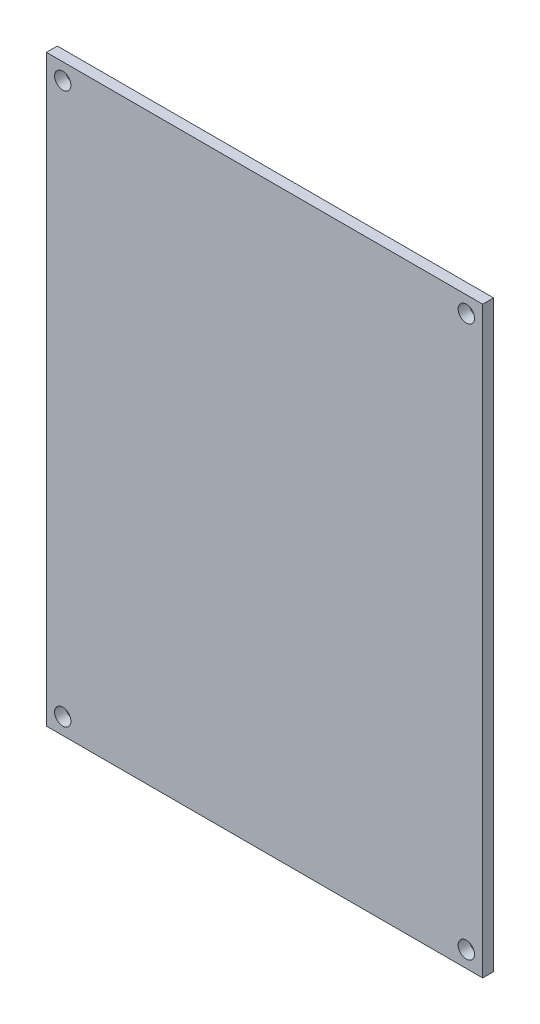
SolidWorks part; units mm, degrees
ref_plane "Ön Düzlem" through (0, 0, 0) normal (0, 0, 1) x (1, 0, 0)
ref_plane "Üst Düzlem" through (0, 0, 0) normal (0, 1, 0) x (1, 0, 0)
ref_plane "Sağ Düzlem" through (0, 0, 0) normal (1, 0, 0) x (0, 0, -1)
sketch "Çizim1" plane through (0, 0, 0) normal (0, 0, 1) x (1, 0, 0)
  line L1 (0, 0) -> (80, 0)
  line L2 (0, 0) -> (0, 107)
  line L3 (0, 107) -> (80, 107)
  line L4 (80, 0) -> (80, 107)
  circle A0 centre (3, 3) radius 1.5
  circle A1 centre (77, 3) radius 1.5
  circle A2 centre (77, 104) radius 1.5
  circle A3 centre (3, 104) radius 1.5
  dimension "D3" = 3
  dimension "D7" = 3
  dimension "D9" = 3
  dimension "D13" = 3
  dimension "D1" = 107
  dimension "D2" = 80
  dimension "D4" = 3
  dimension "D5" = 3
  dimension "D6" = 3
  dimension "D8" = 3
  dimension "D10" = 3
  dimension "D11" = 3
  dimension "D12" = 3
  dimension "D14" = 3
extrude "Yükseklik-Ekstrüzyon1" add sketch "Çizim1" along normal blind 2
